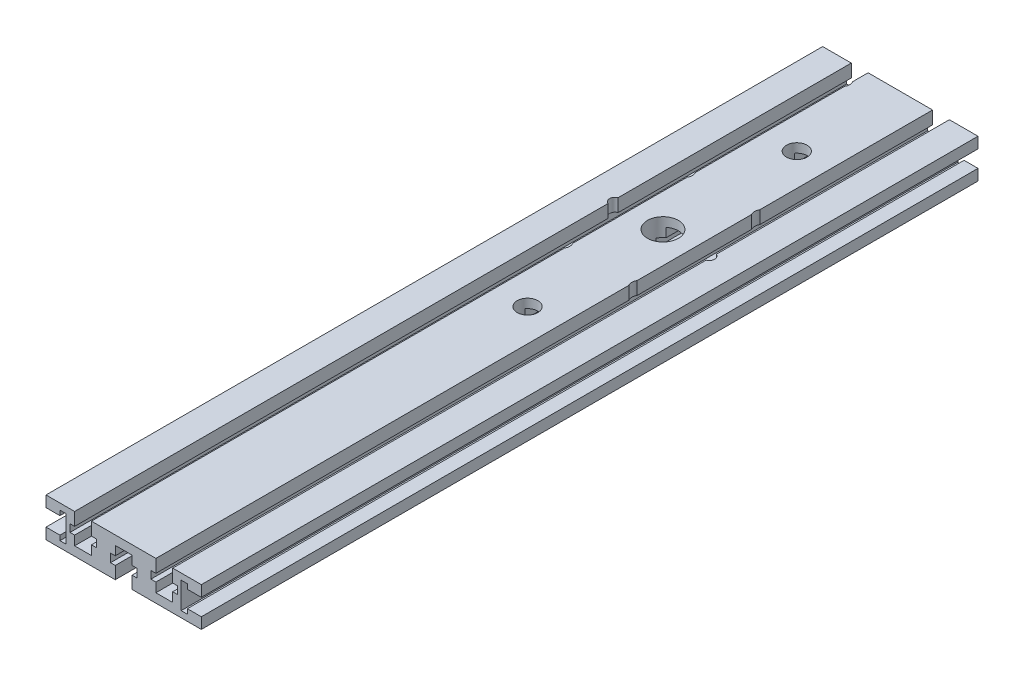
SolidWorks part; units mm, degrees
ref_plane "前视" through (0, 0, 0) normal (0, 0, 1) x (1, 0, 0)
ref_plane "上视" through (0, 0, 0) normal (0, 1, 0) x (1, 0, 0)
ref_plane "右视" through (0, 0, 0) normal (1, 0, 0) x (0, 0, -1)
sketch "草图1" plane through (0, 0, 0) normal (0, 0, 1) x (1, 0, 0)
  line L0 (0, 0) -> (26.75, 0)
  line L1 (0, 0) -> (0, 4.25)
  line L2 (0, 4.25) -> (5.3867, 4.25)
  line L3 (5.3867, 4.25) -> (5.3867, 2.4)
  line L4 (5.3867, 2.4) -> (7.8, 2.4)
  line L5 (7.8, 2.4) -> (7.8, 12.6)
  line L6 (7.8, 12.6) -> (5.3867, 12.6)
  line L7 (5.3867, 12.6) -> (5.3867, 10.75)
  line L8 (5.3867, 10.75) -> (0, 10.75)
  line L9 (0, 10.75) -> (0, 15)
  line L10 (0, 15) -> (11.0524, 15)
  line L11 (11.0524, 15) -> (11.0524, 10.0038)
  line L12 (11.0524, 10.0038) -> (9.2662, 10.0038)
  line L13 (9.2662, 10.0038) -> (9.2662, 7.0947)
  line L14 (9.2662, 7.0947) -> (11.0524, 7.0947)
  line L15 (11.0524, 7.0947) -> (11.0524, 3.5)
  line L16 (11.0524, 3.5) -> (17.5524, 3.5)
  line L17 (17.5524, 3.5) -> (17.5524, 7.0947)
  line L18 (17.5524, 7.0947) -> (19.4662, 7.0947)
  line L19 (19.4662, 7.0947) -> (19.4662, 10.0038)
  line L20 (19.4662, 10.0038) -> (17.5524, 10.0038)
  line L21 (17.5524, 10.0038) -> (17.5524, 15)
  line L22 (17.5524, 15) -> (30, 15)
  line L23 (26.75, 0) -> (26.75, 4.7964)
  line L24 (26.75, 4.7964) -> (24.9265, 4.7964)
  line L25 (24.9265, 4.7964) -> (24.9265, 8.0234)
  line L26 (24.9265, 8.0234) -> (26.75, 8.0234)
  line L27 (26.75, 8.0234) -> (26.75, 11.5)
  line L28 (26.75, 11.5) -> (30, 11.5)
  line L29 (30, 15) -> (42.4476, 15)
  line L30 (30, 11.5) -> (33.25, 11.5)
  line L32 (33.25, 8.0234) -> (33.25, 11.5)
  line L33 (35.0735, 8.0234) -> (33.25, 8.0234)
  line L34 (35.0735, 4.7964) -> (35.0735, 8.0234)
  line L35 (33.25, 4.7964) -> (35.0735, 4.7964)
  line L36 (33.25, 0) -> (33.25, 4.7964)
  line L37 (42.4476, 10.0038) -> (42.4476, 15)
  line L38 (40.5338, 10.0038) -> (42.4476, 10.0038)
  line L39 (40.5338, 7.0947) -> (40.5338, 10.0038)
  line L40 (42.4476, 7.0947) -> (40.5338, 7.0947)
  line L41 (42.4476, 3.5) -> (42.4476, 7.0947)
  line L42 (48.9476, 3.5) -> (42.4476, 3.5)
  line L43 (48.9476, 7.0947) -> (48.9476, 3.5)
  line L44 (50.7338, 7.0947) -> (48.9476, 7.0947)
  line L45 (50.7338, 10.0038) -> (50.7338, 7.0947)
  line L46 (48.9476, 10.0038) -> (50.7338, 10.0038)
  line L47 (48.9476, 15) -> (48.9476, 10.0038)
  line L48 (60, 15) -> (48.9476, 15)
  line L49 (60, 10.75) -> (60, 15)
  line L50 (54.6133, 10.75) -> (60, 10.75)
  line L51 (54.6133, 12.6) -> (54.6133, 10.75)
  line L52 (52.2, 12.6) -> (54.6133, 12.6)
  line L53 (52.2, 2.4) -> (52.2, 12.6)
  line L54 (54.6133, 2.4) -> (52.2, 2.4)
  line L55 (54.6133, 4.25) -> (54.6133, 2.4)
  line L56 (60, 4.25) -> (54.6133, 4.25)
  line L57 (60, 0) -> (60, 4.25)
  line L58 (60, 0) -> (33.25, 0)
  dimension "D1" = 6.5
  dimension "D2" = 7.8
  dimension "D3" = 15
  dimension "D4" = 6.5
  dimension "D5" = 11.5
  dimension "D6" = 2.4
  dimension "D7" = 10.2
  dimension "D8" = 15
  dimension "D9" = 2.4
  dimension "D10" = 4.25
  dimension "D11" = 11.5
  dimension "D12" = 60
  dimension "D13" = 3.25
extrude "凸台-拉伸1" add sketch "草图1" along normal blind 300
hole_wizard "Ø12.0 (12) 直径孔1" positions "草图3" profile "草图2" hole size "Ø12.0" standard "Gb" end condition through all
sketch "草图3" plane through (0, 15, 0) normal (0, 1, 0) x (1, 0, 0)
  line L0 (42.4476, -300) -> (17.5524, -300) construction
  point P0 (30.3155, -92)
  dimension "D1" = 208
sketch "草图2" plane through (30.3155, 15, 92) normal (1, 0, 0) x (0, 0, 1)
  line L0 (0, 0) -> (0, 15)
  line L1 (0, 15) -> (6, 15)
  line L2 (6, 15) -> (6, 0)
  line L5 (6, 0) -> (0, 0)
  line L11 (0, -6.35) -> (0, 107.95) construction
  dimension "通孔孔直径" = 12
  dimension "通孔孔深度" = 15
hole_wizard "Ø8.0 (8) 直径孔1" positions "草图5" profile "草图4" hole size "Ø8.0" standard "Gb" end condition through all
sketch "草图5" plane through (0, 15, 0) normal (0, 1, 0) x (1, 0, 0)
  line L0 (0, -300) -> (0, 0) construction
  line L7 (42.4476, -300) -> (17.5524, -300) construction
  point P0 (30, -40)
  point P2 (30, -144)
  point P30 (30, -300)
  dimension "D1" = 30
  dimension "D2" = 260
  dimension "D3" = 156
sketch "草图4" plane through (30, 15, 40) normal (1, 0, 0) x (0, 0, 1)
  line L0 (0, 0) -> (0, 15)
  line L1 (0, 15) -> (4, 15)
  line L2 (4, 15) -> (4, 0)
  line L5 (4, 0) -> (0, 0)
  line L11 (0, -6.35) -> (0, 107.95) construction
  dimension "通孔孔直径" = 8
  dimension "通孔孔深度" = 15
hole_wizard "Ø6.0 (6) 直径孔2" positions "草图9" profile "草图8" hole size "Ø6.0" standard "Gb" end condition through all
sketch "草图9" plane through (0, 0, 0) normal (0, -1, 0) x (-1, 0, 0)
  line L0 (0, 0) -> (-26.75, 0) construction
  line L1 (0, -300) -> (-26.75, -300) construction
  line L2 (-60, -300) -> (-60, 0) construction
  line L3 (0, -300) -> (0, 0) construction
  point P0 (-15, -7.5)
  point P2 (-15, -68.3)
  point P4 (-15, -115.7)
  point P6 (-45, -68.3)
  point P8 (-45, -115.7)
  dimension "D1" = 7.5
  dimension "D2" = 231.7
  dimension "D3" = 184.3
  dimension "D4" = 15
  dimension "D5" = 15
sketch "草图8" plane through (15, 0, 7.5) normal (1, 0, 0) x (0, 0, -1)
  line L0 (0, 0) -> (0, 15)
  line L1 (0, 15) -> (3, 15)
  line L2 (3, 15) -> (3, 0)
  line L5 (3, 0) -> (0, 0)
  line L11 (0, -6.35) -> (0, 107.95) construction
  dimension "通孔孔直径" = 6
  dimension "通孔孔深度" = 15
hole_wizard "M5 螺纹孔的螺纹孔钻头1" positions "草图11" profile "草图10" hole size "M5" standard "Gb" end condition through all
sketch "草图11" plane through (0, 0, 0) normal (0, -1, 0) x (-1, 0, 0)
  line L0 (-60, -300) -> (-60, 0) construction
  line L1 (-33.25, -300) -> (-60, -300) construction
  line L2 (0, -300) -> (0, 0) construction
  point P0 (-48.2, -92)
  point P2 (-11.8, -92)
  dimension "D1" = 11.8
  dimension "D2" = 208
  dimension "D3" = 11.8
sketch "草图10" plane through (48.2, 0, 92) normal (1, 0, 0) x (0, 0, -1)
  line L0 (0, 0) -> (0, 15)
  line L1 (0, 15) -> (2.1, 15)
  line L2 (2.1, 15) -> (2.1, 0)
  line L5 (2.1, 0) -> (0, 0)
  line L11 (0, -6.35) -> (0, 107.95) construction
  dimension "通孔孔直径" = 4.2
  dimension "通孔孔深度" = 15
